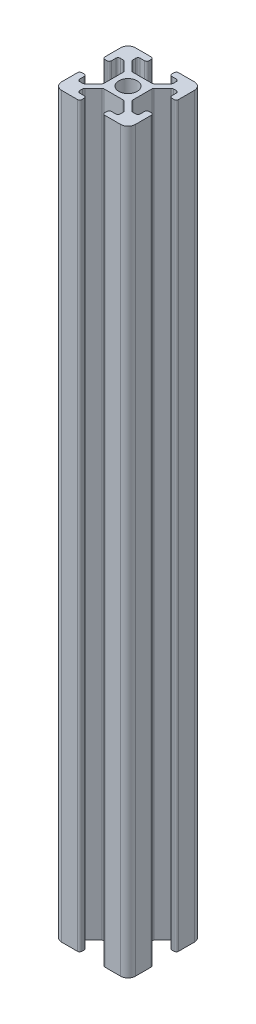
SolidWorks part; units mm, degrees
ref_plane "前视基准面" through (0, 0, 0) normal (0, 0, 1) x (1, 0, 0)
ref_plane "上视基准面" through (0, 0, 0) normal (0, 1, 0) x (1, 0, 0)
ref_plane "右视基准面" through (0, 0, 0) normal (1, 0, 0) x (0, 0, -1)
sketch "草图1" plane through (0, 0, 0) normal (0, 1, 0) x (1, 0, 0)
  line L0 (3.1, 8.8) -> (3.1, 9.4)
  line L1 (-10, -10) -> (10, -10) construction
  line L2 (-10, -10) -> (-10, 10) construction
  line L3 (-10, 10) -> (10, 10) construction
  line L4 (10, -10) -> (10, 10) construction
  line L5 (-10, -10) -> (10, 10) construction
  line L6 (-10, 10) -> (10, -10) construction
  line L7 (3.7, 10) -> (8, 10)
  line L8 (0, 10) -> (0, -10) construction
  line L9 (3.7, 8.2) -> (4.9, 8.2)
  line L10 (5.3243, 6.3849) -> (3.0151, 4.0757)
  line L11 (2.5908, 3.9) -> (0, 3.9)
  line L12 (5.5, 7.6) -> (5.5, 6.8092)
  line L13 (10, 3.7) -> (10, 8)
  line L14 (8.8, 3.1) -> (9.4, 3.1)
  line L15 (8.2, 3.7) -> (8.2, 4.9)
  line L16 (7.6, 5.5) -> (6.8092, 5.5)
  line L17 (6.3849, 5.3243) -> (4.0757, 3.0151)
  line L18 (3.9, 2.5908) -> (3.9, 0)
  line L19 (3.9, -2.5908) -> (3.9, 0)
  line L20 (2.5908, -3.9) -> (0, -3.9)
  line L21 (5.3243, -6.3849) -> (3.0151, -4.0757)
  line L22 (6.3849, -5.3243) -> (4.0757, -3.0151)
  line L23 (5.5, -7.6) -> (5.5, -6.8092)
  line L24 (3.7, -8.2) -> (4.9, -8.2)
  line L25 (3.1, -8.8) -> (3.1, -9.4)
  line L26 (3.7, -10) -> (8, -10)
  line L27 (10, -3.7) -> (10, -8)
  line L28 (8.8, -3.1) -> (9.4, -3.1)
  line L29 (8.2, -3.7) -> (8.2, -4.9)
  line L30 (7.6, -5.5) -> (6.8092, -5.5)
  line L31 (-2.5908, -3.9) -> (0, -3.9)
  line L32 (-3.9, -2.5908) -> (-3.9, 0)
  line L33 (-6.3849, -5.3243) -> (-4.0757, -3.0151)
  line L34 (-5.3243, -6.3849) -> (-3.0151, -4.0757)
  line L35 (-7.6, -5.5) -> (-6.8092, -5.5)
  line L36 (-8.2, -3.7) -> (-8.2, -4.9)
  line L37 (-8.8, -3.1) -> (-9.4, -3.1)
  line L38 (-10, -3.7) -> (-10, -8)
  line L39 (-3.7, -10) -> (-8, -10)
  line L40 (-3.1, -8.8) -> (-3.1, -9.4)
  line L41 (-3.7, -8.2) -> (-4.9, -8.2)
  line L42 (-5.5, -7.6) -> (-5.5, -6.8092)
  line L43 (-3.9, 2.5908) -> (-3.9, 0)
  line L44 (-2.5908, 3.9) -> (0, 3.9)
  line L45 (-5.3243, 6.3849) -> (-3.0151, 4.0757)
  line L46 (-6.3849, 5.3243) -> (-4.0757, 3.0151)
  line L47 (-5.5, 7.6) -> (-5.5, 6.8092)
  line L48 (-3.7, 8.2) -> (-4.9, 8.2)
  line L49 (-3.1, 8.8) -> (-3.1, 9.4)
  line L50 (-3.7, 10) -> (-8, 10)
  line L51 (-10, 3.7) -> (-10, 8)
  line L52 (-8.8, 3.1) -> (-9.4, 3.1)
  line L53 (-8.2, 3.7) -> (-8.2, 4.9)
  line L54 (-7.6, 5.5) -> (-6.8092, 5.5)
  circle A0 centre (0, 0) radius 2.5
  arc A1 (3.0151, 4.0757) -> (2.5908, 3.9) centre (2.5908, 4.5) cw
  arc A2 (5.5, 6.8092) -> (5.3243, 6.3849) centre (4.9, 6.8092) cw
  arc A3 (5.5, 7.6) -> (4.9, 8.2) centre (4.9, 7.6) ccw
  arc A4 (3.1, 8.8) -> (3.7, 8.2) centre (3.7, 8.8) ccw
  arc A5 (3.7, 10) -> (3.1, 9.4) centre (3.7, 9.4) ccw
  arc A6 (10, 3.7) -> (9.4, 3.1) centre (9.4, 3.7) cw
  arc A7 (8.8, 3.1) -> (8.2, 3.7) centre (8.8, 3.7) cw
  arc A8 (7.6, 5.5) -> (8.2, 4.9) centre (7.6, 4.9) cw
  arc A9 (6.8092, 5.5) -> (6.3849, 5.3243) centre (6.8092, 4.9) ccw
  arc A10 (4.0757, 3.0151) -> (3.9, 2.5908) centre (4.5, 2.5908) ccw
  arc A11 (10, 8) -> (8, 10) centre (8, 8) ccw
  arc A12 (3.0151, -4.0757) -> (2.5908, -3.9) centre (2.5908, -4.5) ccw
  arc A13 (4.0757, -3.0151) -> (3.9, -2.5908) centre (4.5, -2.5908) cw
  arc A14 (5.5, -6.8092) -> (5.3243, -6.3849) centre (4.9, -6.8092) ccw
  arc A15 (6.8092, -5.5) -> (6.3849, -5.3243) centre (6.8092, -4.9) cw
  arc A16 (5.5, -7.6) -> (4.9, -8.2) centre (4.9, -7.6) cw
  arc A17 (3.1, -8.8) -> (3.7, -8.2) centre (3.7, -8.8) cw
  arc A18 (3.7, -10) -> (3.1, -9.4) centre (3.7, -9.4) cw
  arc A19 (8, -10) -> (10, -8) centre (8, -8) ccw
  arc A20 (10, -3.7) -> (9.4, -3.1) centre (9.4, -3.7) ccw
  arc A21 (8.8, -3.1) -> (8.2, -3.7) centre (8.8, -3.7) ccw
  arc A22 (7.6, -5.5) -> (8.2, -4.9) centre (7.6, -4.9) ccw
  arc A23 (-4.0757, -3.0151) -> (-3.9, -2.5908) centre (-4.5, -2.5908) ccw
  arc A24 (-3.0151, -4.0757) -> (-2.5908, -3.9) centre (-2.5908, -4.5) cw
  arc A25 (-6.8092, -5.5) -> (-6.3849, -5.3243) centre (-6.8092, -4.9) ccw
  arc A26 (-5.5, -6.8092) -> (-5.3243, -6.3849) centre (-4.9, -6.8092) cw
  arc A27 (-7.6, -5.5) -> (-8.2, -4.9) centre (-7.6, -4.9) cw
  arc A28 (-8.8, -3.1) -> (-8.2, -3.7) centre (-8.8, -3.7) cw
  arc A29 (-10, -3.7) -> (-9.4, -3.1) centre (-9.4, -3.7) cw
  arc A30 (-10, -8) -> (-8, -10) centre (-8, -8) ccw
  arc A31 (-3.7, -10) -> (-3.1, -9.4) centre (-3.7, -9.4) ccw
  arc A32 (-3.1, -8.8) -> (-3.7, -8.2) centre (-3.7, -8.8) ccw
  arc A33 (-5.5, -7.6) -> (-4.9, -8.2) centre (-4.9, -7.6) ccw
  arc A34 (-3.0151, 4.0757) -> (-2.5908, 3.9) centre (-2.5908, 4.5) ccw
  arc A35 (-4.0757, 3.0151) -> (-3.9, 2.5908) centre (-4.5, 2.5908) cw
  arc A36 (-5.5, 6.8092) -> (-5.3243, 6.3849) centre (-4.9, 6.8092) ccw
  arc A37 (-6.8092, 5.5) -> (-6.3849, 5.3243) centre (-6.8092, 4.9) cw
  arc A38 (-5.5, 7.6) -> (-4.9, 8.2) centre (-4.9, 7.6) cw
  arc A39 (-3.1, 8.8) -> (-3.7, 8.2) centre (-3.7, 8.8) cw
  arc A40 (-3.7, 10) -> (-3.1, 9.4) centre (-3.7, 9.4) cw
  arc A41 (-8, 10) -> (-10, 8) centre (-8, 8) ccw
  arc A42 (-10, 3.7) -> (-9.4, 3.1) centre (-9.4, 3.7) ccw
  arc A43 (-8.8, 3.1) -> (-8.2, 3.7) centre (-8.8, 3.7) ccw
  arc A44 (-7.6, 5.5) -> (-8.2, 4.9) centre (-7.6, 4.9) ccw
  point P0 (0, 0)
  point P20 (5.5, 6.5607)
  point P25 (3.1, 8.2)
  point P28 (3.1, 10)
  point P156 (0, 0)
  dimension "D3" = 5
  dimension "D9" = 0.6
  dimension "D10" = 2
  dimension "D1" = 20
  dimension "D2" = 20
  dimension "D4" = 6.1
  dimension "D5" = 1.5
  dimension "D6" = 1.8
  dimension "D7" = 3.1
  dimension "D8" = 4.5
  dimension "D11" = 4
extrude "凸台-拉伸1" add sketch "草图1" along normal blind 200
